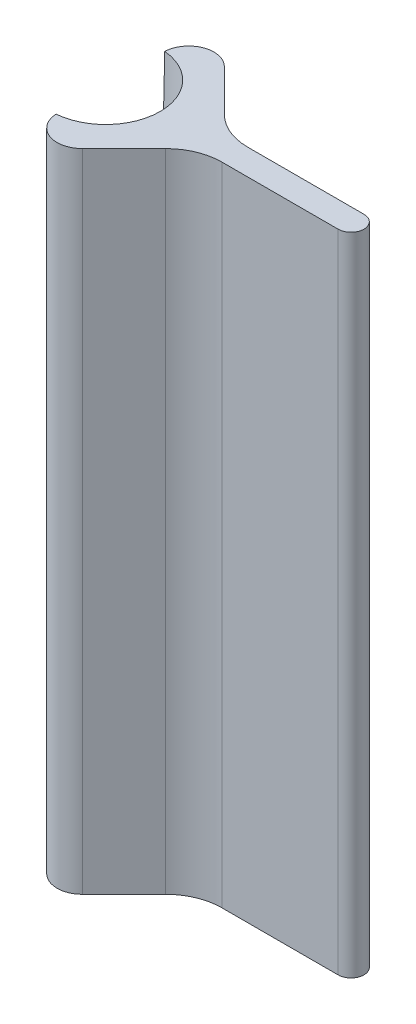
SolidWorks part; units mm, degrees
ref_plane "Front Plane" through (0, 0, 0) normal (0, 0, 1) x (1, 0, 0)
ref_plane "Top Plane" through (0, 0, 0) normal (0, 1, 0) x (1, 0, 0)
ref_plane "Right Plane" through (0, 0, 0) normal (1, 0, 0) x (0, 0, -1)
sketch "Sketch2" plane through (0, 0, 0) normal (0, 1, 0) x (1, 0, 0)
  line L0 (0, 0) -> (4, 0) construction
  line L1 (0, 0) -> (0.0553, 0.6326) construction
  line L2 (0.0553, 0.6326) -> (0.0751, 0.8586)
  line L3 (0.7385, 1.1) -> (1.3828, 0.4556)
  line L5 (4, 0.2) -> (4, 0) construction
  line L7 (0.7385, -1.1) -> (1.3828, -0.4556)
  line L8 (0.0553, -0.6326) -> (0.0751, -0.8586)
  line L9 (0.0553, 0.6326) -> (0.0553, -0.6326)
  line L15 (0, 0) -> (0.9192, -0.9192) construction
  line L16 (2, -0.2) -> (3.8, -0.2)
  line L19 (2, 0.2) -> (3.8, 0.2)
  circle A0 centre (0, 0) radius 0.635 construction
  arc A2 (0.0751, 0.8586) -> (0.7385, 1.1) centre (0.4631, 0.8246) cw
  arc A3 (1.3828, 0.4556) -> (2, 0.2) centre (2, 1.0728) ccw
  arc A4 (1.3828, -0.4556) -> (2, -0.2) centre (2, -1.0728) cw
  arc A5 (0.0751, -0.8586) -> (0.7385, -1.1) centre (0.4631, -0.8246) ccw
  arc A7 (3.8, 0.2) -> (3.8, -0.2) centre (3.8, 0) cw
  point P27 (4, -0.2)
  dimension "D1" = 1.27
  dimension "D7" = 1.1
  dimension "D5" = 1.3
  dimension "D2" = 4
  dimension "D3" = 95
  dimension "D4" = 0.2
  dimension "D6" = 45
  dimension "D8" = 2
  dimension "D9" = 0.8246
extrude "Boss-Extrude2" add sketch "Sketch2" along normal blind 10
sketch "Sketch5" plane through (0, 0, 0) normal (0, -1, 0) x (1, 0, 0)
  circle A0 centre (0, 0) radius 0.635
  circle A1 centre (0, 0) radius 0.635 construction
extrude "Cut-Extrude1" cut sketch "Sketch5" against normal up to next (10 mm away) draft 1.2 draft outward yes
